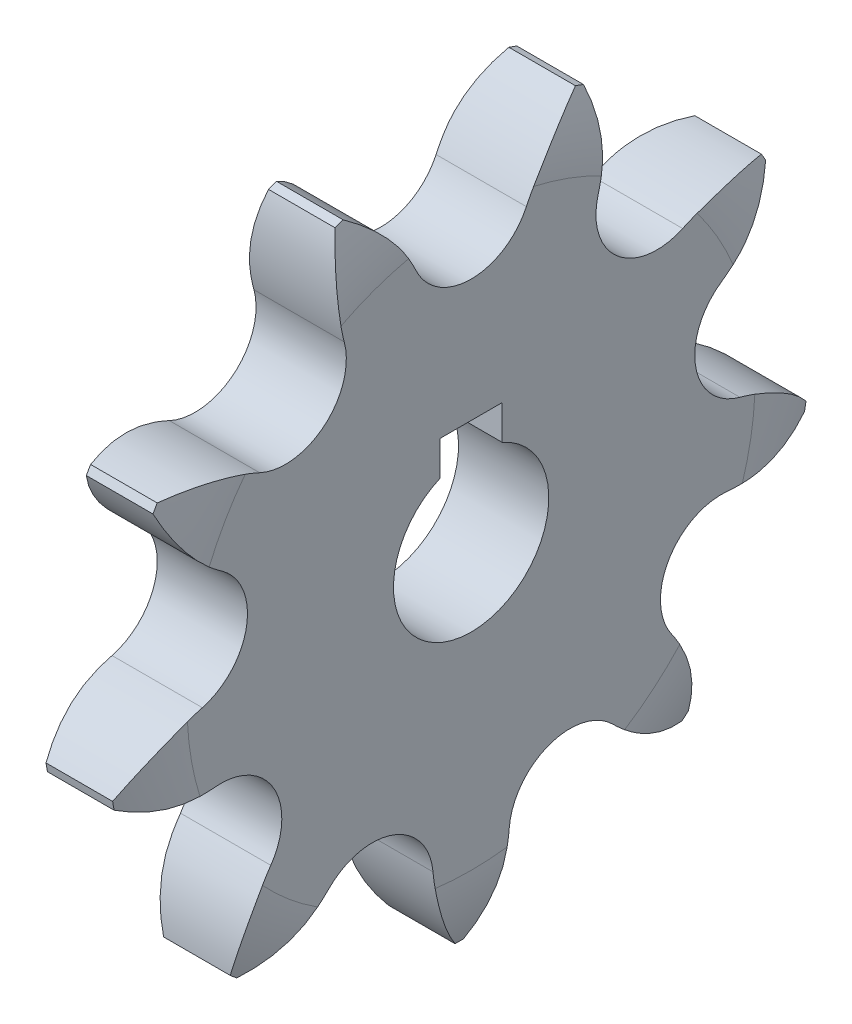
SolidWorks part; units mm, degrees
ref_plane "Plane1" through (0, 0, 0) normal (0, 0, 1) x (1, 0, 0)
ref_plane "Plane2" through (0, 0, 0) normal (0, 1, 0) x (1, 0, 0)
ref_plane "Plane3" through (0, 0, 0) normal (1, 0, 0) x (0, 0, -1)
other "Configuration Table"
sketch "Clipboard" plane through (0, 0, 0) normal (0, 1, 0) x (1, 0, 0)
  line L0 (0, 0) -> (12.5436, -1.9867)
  line L1 (-15, 0) -> (100, 0) construction
  line L2 (0, 0) -> (-0.5049, 0.5707)
  line L3 (0, 0) -> (-11.863, 4.5341)
  line L4 (0, 0) -> (3.0618, 0.4849)
  line L5 (0, 0) -> (-46.8476, -17.4728)
  line L6 (0, 0) -> (-4.8183, -3.251)
  line L7 (-0.5049, 0.5707) -> (48.7359, 9.2532)
  line L8 (-76.2, 38.1) -> (-74.4, 38.1)
  line L9 (-73.3479, 40.976) -> (-72.751, 41.0367)
  line L10 (-73.1375, 10.4807) -> (-60.1375, 10.4807)
  circle A0 centre (0, 0) radius 3.885
  circle A1 centre (0, 0) radius 11.9133
  circle A2 centre (0, 0) radius 37.5
  dimension "Dr" = 7.77
  dimension "MHD" = 23.8266
  dimension "Hub_dia" = 75
  dimension "Num_teeth" = 9
  dimension "Pitch" = 12.7
  dimension "Width" = 3.1
  dimension "Side_relief" = 0.762
  dimension "Side_radius" = 12.7
  dimension "Overall_len" = 50
  dimension "Show_teeth" = 9
  dimension "Thickness" = 5.8125
  dimension "OAL" = 50.0005
  dimension "T_dim" = 1.8
  dimension "Fillet_rad" = 0.6
  dimension "Face_width" = 5.813
  dimension "Num_strands" = 1
  dimension "Transv_pitch" = 13
  dimension "Plate_wid" = 9.91
sketch "BasProSke" plane through (0, 0, 0) normal (0, 1, 0) x (1, 0, 0)
  line L0 (-10, 0) -> (60, 0) construction
  line L1 (0, 0) -> (0, 18.2857)
  line L2 (0, 0) -> (5.8125, 0)
  line L3 (5.8125, 0) -> (5.8125, 18.2857)
  line L4 (5.0505, 22.6187) -> (0.762, 22.6187)
  arc A0 (0, 18.2857) -> (0.762, 22.6187) centre (12.7, 18.2857) cw
  arc A1 (5.8125, 18.2857) -> (5.0505, 22.6187) centre (-6.8875, 18.2857) ccw
  dimension "Thickness" = 5.8125
  dimension "D1" = 12.7
  dimension "G1" = 0.762
  dimension "G2" = 0.762
  dimension "Diameter" = 45.2373
revolve "Base-Revolve" add sketch "BasProSke" angle 360 about L0
sketch "TooCutSke" plane through (0, 0, 0) normal (1, 0, 0) x (0, 0, -1)
  line L0 (0, 18.605) -> (3.5562, 16.9467) construction
  line L1 (0, 0) -> (0, 107) construction
  line L2 (0, 18.605) -> (-10, 18.605) construction
  line L3 (0, 18.605) -> (-3.5562, 16.9467) construction
  arc A0 (3.5562, 16.9467) -> (8.0463, 21.6732) centre (12.8517, 12.6122) cw
  arc A1 (3.5562, 16.9467) -> (-3.5562, 16.9467) centre (0, 18.605) cw
  arc A2 (-3.5562, 16.9467) -> (-8.0463, 21.6732) centre (-12.8517, 12.6122) ccw
  arc A3 (8.0463, 21.6732) -> (-8.0463, 21.6732) centre (0, 0) ccw
  dimension "R1" = 3.9238
  dimension "R2" = 10.2564
  dimension "Overcut" = 23.1187
  dimension "Seat_radius" = 18.605
  dimension "X" = 130
extrude "ToothCut" cut sketch "TooCutSke" along normal through all
pattern_circular "TeethCuts" count 9 every 40 about axis through (-10, 0, 0) along (1, 0, 0) of "ToothCut"
sketch "HubNeaOneSke" plane through (0, 0, 0) normal (-1, 0, 0) x (0, 0, 1)
  circle A0 centre (0, 0) radius 11.9133
  dimension "Diameter" = 23.8266
extrude "HubNearOne" [suppressed] add sketch "HubNeaOneSke" along normal blind 44.188
fillet "HubNearOneFillet" [suppressed] radius 0.6
sketch "HubNeaBotSke" plane through (0, 0, 0) normal (-1, 0, 0) x (0, 0, 1)
  circle A0 centre (0, 0) radius 11.9133
  dimension "Diameter" = 23.8266
extrude "HubNearBoth" [suppressed] add sketch "HubNeaBotSke" along normal blind 22.094
fillet "HubNearBothFillet" [suppressed] radius 0.6
ref_plane "FarPln" through (5.8125, 0, 0) normal (1, 0, 0) x (0, 0, -1)
sketch "HubFarSke" plane through (5.8125, 0, 0) normal (1, 0, 0) x (0, 0, -1)
  circle A0 centre (0, 0) radius 11.9133
  dimension "Diameter" = 23.8266
extrude "HubFar" [suppressed] add sketch "HubFarSke" along normal blind 22.094
fillet "HubFarFillet" [suppressed] radius 0.6
sketch "BorSke" plane through (0, 0, 0) normal (1, 0, 0) x (0, 0, -1)
  circle A0 centre (0, 0) radius 5
  dimension "Diameter" = 10
extrude "Bore" cut sketch "BorSke" along normal mid plane 100.001
sketch "KeySke" plane through (0, 0, 0) normal (1, 0, 0) x (0, 0, -1)
  line L0 (-2, 0) -> (-2, 6.8)
  line L1 (-2, 6.8) -> (2, 6.8)
  line L2 (2, 6.8) -> (2, 0)
  line L3 (0, 0) -> (0, 34) construction
  line L4 (-2, 0) -> (2, 0)
  dimension "Offset" = 6.8
  dimension "Width" = 4
extrude "Keyway" cut sketch "KeySke" along normal mid plane 100.001
pattern_circular "Keyway2" [suppressed] count 2 every 90 about axis through (-10, 0, 0) along (1, 0, 0)
equation "' \"Pitch@Clipboard\" = 12.7"
equation "' \"Num_strands@Clipboard\" = 1"
equation "' \"Num_teeth@Clipboard\" = 9"
equation "' \"Hub_dia@Clipboard\" = 50"
equation "' \"Overall_len@Clipboard\" = 3"
equation "' \"Diameter@BorSke\" = 12"
equation "' \"T_dim@Clipboard\" = 1"
equation "' \"Width@KeySke\" = 2"
equation "' \"Dr@Clipboard\" = 8.51"
equation "' \"Face_width@Clipboard\" = 7.2"
equation "' \"Side_radius@Clipboard\" = 12.7"
equation "' \"Side_relief@Clipboard\" = 1.27"
equation "' \"Transv_pitch@Clipboard\" = 13.92"
equation "' \"Show_teeth@Clipboard\" = 9"
equation "' \"Fillet_rad@Clipboard\" = 0.6"
equation "' \"Plate_wid@Clipboard\" = 11.8"
equation "\"Num_teeth@Clipboard\" = int( \"Num_teeth@Clipboard\" )"
equation "\"Num_teeth@Clipboard\" = ((sgn( \"Num_teeth@Clipboard\" - 5.0)+1)*( \"Num_teeth@Clipboard\" - 5.0))/2 +5.0"
equation "\"Num_teeth@Clipboard\" = ((sgn( \"Num_teeth@Clipboard\" - 200.0)-1)*( \"Num_teeth@Clipboard\" - 200.0))/-2 +200.0"
equation "\"MHD@Clipboard\" = \"Pitch@Clipboard\" * (1.0 / tan(3.14159265 / \"Num_teeth@Clipboard\" )) - 1.04 * \"Plate_wid@Clipboard\" - 0.76"
equation "\"Thickness@Clipboard\"  = \"Face_width@Clipboard\" + (\"Num_strands@Clipboard\" - 1) * \"Transv_pitch@Clipboard\""
equation "\"OAL@Clipboard\" = \"Thickness@Clipboard\" + 2 * \"Fillet_rad@Clipboard\" + 1"
equation "\"MHD@Clipboard\" = ((sgn( \"MHD@Clipboard\" - \"Hub_dia@Clipboard\" )-1)*( \"MHD@Clipboard\" - \"Hub_dia@Clipboard\" ))/-2+ \"Hub_dia@Clipboard\""
equation "\"OAL@Clipboard\" = ((sgn( \"OAL@Clipboard\" - \"Overall_len@Clipboard\" )+1)*( \"OAL@Clipboard\" - \"Overall_len@Clipboard\" ))/2 + \"Overall_len@Clipboard\" + 0.0005"
equation "\"Num_teeth@TeethCuts\" = int( \"Show_teeth@Clipboard\" ) + 1"
equation "\"Num_teeth@TeethCuts\" = ((sgn( \"Num_teeth@TeethCuts\" - \"Num_teeth@Clipboard\" )-1)*( \"Num_teeth@TeethCuts\" - \"Num_teeth@Clipboard\" ))/-2+ \"Num_teeth@Clipboard\""
equation "\"Num_teeth@TeethCuts\" = ((sgn( \"Num_teeth@TeethCuts\" - 2.0)+1)*( \"Num_teeth@TeethCuts\" - 2.0))/2 +2.0"
equation "\"Angle@TeethCuts\" = 360.0 / \"Num_teeth@Clipboard\""
equation "\"Seat_radius@TooCutSke\" = ( \"Pitch@Clipboard\" / 2.0) / sin(3.14159265 / \"Num_teeth@Clipboard\" ) - \"Dr@Clipboard\" / 2.0 + \"Dr@Clipboard\" * 0.505"
equation "\"R1@TooCutSke\"  = \"Dr@Clipboard\" * 0.505"
equation "\"X@TooCutSke\" = 140.0 - (90.0 / \"Num_teeth@Clipboard\")"
equation "\"R2@TooCutSke\" = 0.12 * \"Dr@Clipboard\" * ( \"Num_teeth@Clipboard\" + 2.0)"
equation "\"Overcut@TooCutSke\" = 0.5 + 0.625 * \"Pitch@Clipboard\" - 0.5 * \"Dr@Clipboard\"  +  \"Pitch@Clipboard\" / 2.0 / sin(3.14159265 / \"Num_teeth@Clipboard\" )"
equation "\"Diameter@BasProSke\" = 2.0 * ( 0.625 * \"Pitch@Clipboard\" - 0.5 * \"Dr@Clipboard\"  +  \"Pitch@Clipboard\" / 2.0 / sin(3.14159265 / \"Num_teeth@Clipboard\" ))"
equation "\"Thickness@BasProSke\"  = \"Thickness@Clipboard\""
equation "\"G1@BasProSke\" =  \"Side_relief@Clipboard\""
equation "\"G2@BasProSke\" =  \"Side_relief@Clipboard\""
equation "\"D1@BasProSke\" =  \"Side_radius@Clipboard\""
equation "\"Diameter@HubNeaOneSke\" = \"MHD@Clipboard\""
equation "\"Length@HubNearOne\" = \"OAL@Clipboard\" - \"Thickness@BasProSke\""
equation "\"Diameter@HubNeaBotSke\" = \"MHD@Clipboard\""
equation "\"Length@HubNearBoth\" = ( \"OAL@Clipboard\" - \"Thickness@BasProSke\" ) / 2.0"
equation "\"D1@HubNearOneFillet\" = \"Fillet_rad@Clipboard\""
equation "\"D1@HubNearBothFillet\" = \"Fillet_rad@Clipboard\""
equation "\"Thickness@FarPln\" = \"Thickness@BasProSke\""
equation "\"Diameter@HubFarSke\" = \"MHD@Clipboard\""
equation "\"Length@HubFar\" = ( \"OAL@Clipboard\" - \"Thickness@BasProSke\" ) / 2.0"
equation "\"D1@HubFarFillet\" = \"Fillet_rad@Clipboard\""
equation "\"D1@Bore\" = \"OAL@Clipboard\" * 2.0"
equation "\"D1@Keyway\" = \"OAL@Clipboard\" * 2.0"
equation "\"Offset@KeySke\" = \"T_dim@Clipboard\" + \"Diameter@BorSke\" / 2.0"
